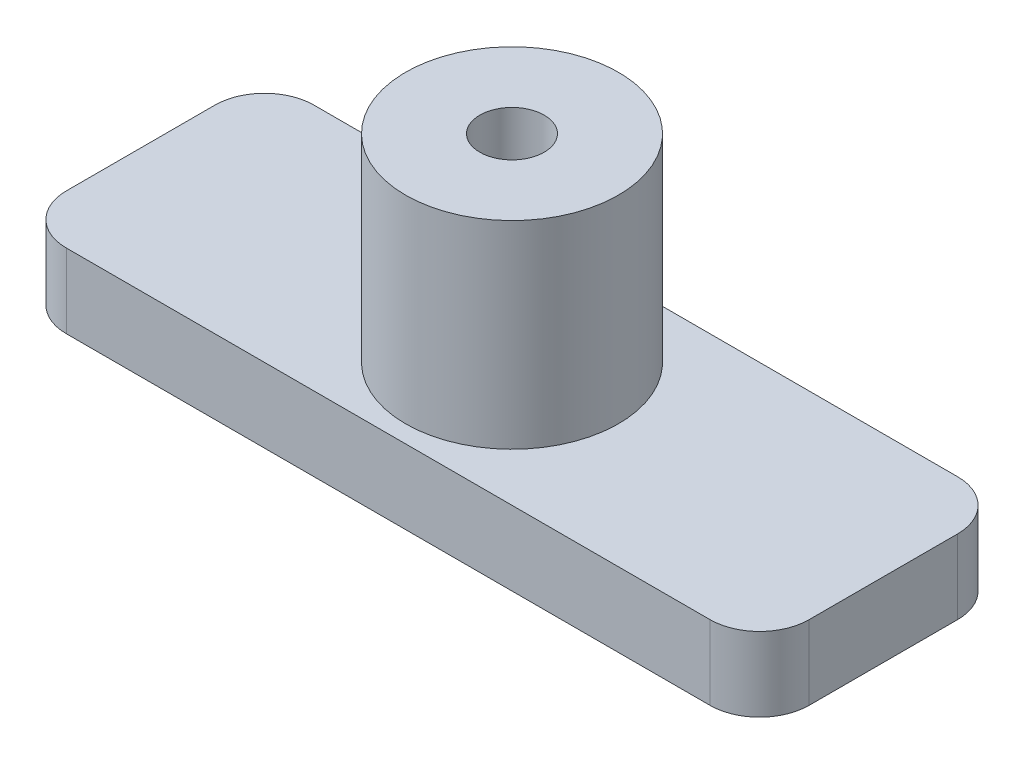
SolidWorks part; units mm, degrees
ref_plane "Front Plane" through (0, 0, 0) normal (0, 0, 1) x (1, 0, 0)
ref_plane "Top Plane" through (0, 0, 0) normal (0, 1, 0) x (1, 0, 0)
ref_plane "Right Plane" through (0, 0, 0) normal (1, 0, 0) x (0, 0, -1)
sketch "Sketch1" plane through (0, 0, 0) normal (0, 1, 0) x (1, 0, 0)
  line L1 (15, -5) -> (-15, -5)
  line L2 (15, -5) -> (15, 5)
  line L3 (15, 5) -> (-15, 5)
  line L4 (-15, -5) -> (-15, 5)
  line L5 (15, -5) -> (-15, 5) construction
  line L6 (15, 5) -> (-15, -5) construction
  point P0 (0, 0)
  dimension "D1" = 30
  dimension "D2" = 10
extrude "Boss-Extrude1" add sketch "Sketch1" along normal blind 3
sketch "Sketch2" plane through (0, 3, 0) normal (0, 1, 0) x (1, 0, 0)
  circle A0 centre (0, 0) radius 4.3
  circle A1 centre (0, 0) radius 1.3
  dimension "D1" = 3
  dimension "D2" = 2.6
extrude "Boss-Extrude2" add sketch "Sketch2" along normal blind 8
fillet "Fillet1" radius 2 4 edges at (15, 1.5, -5) (15, 1.5, 5) (-15, 1.5, -5) (-15, 1.5, 5)
